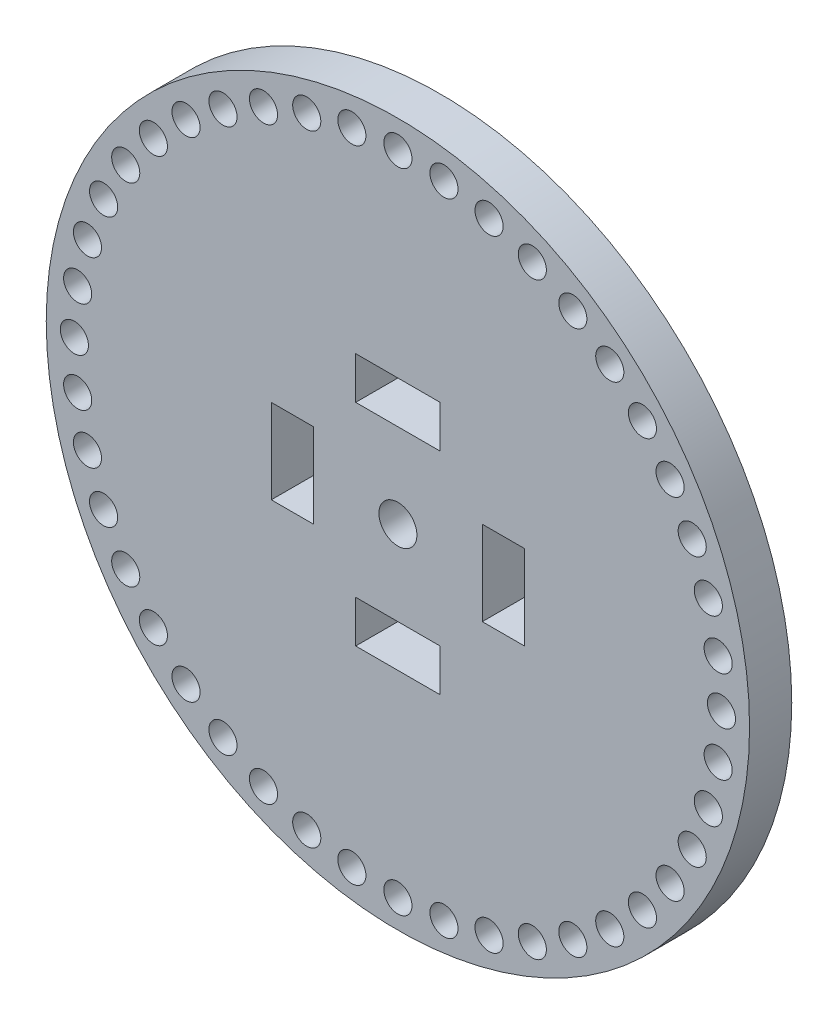
SolidWorks part; units mm, degrees
ref_plane "Front Plane" through (0, 0, 0) normal (0, 0, 1) x (1, 0, 0)
ref_plane "Top Plane" through (0, 0, 0) normal (0, 1, 0) x (1, 0, 0)
ref_plane "Right Plane" through (0, 0, 0) normal (1, 0, 0) x (0, 0, -1)
sketch "Sketch1" plane through (0, 0, 0) normal (0, 0, 1) x (1, 0, 0)
  line L0 (0, 0) -> (0, 9.75) construction
  circle A0 centre (0, 0) radius 25
  point P8 (0, 8.25)
  dimension "D1" = 50
extrude "Boss-Extrude1" add sketch "Sketch1" along normal blind 3
sketch "Sketch6" plane through (0, 0, 3) normal (0, 0, 1) x (1, 0, 0)
  line L0 (0, 0) -> (0, 23) construction
  circle A0 centre (0, 23) radius 1
  circle A1 centre (3.2732, 22.7659) radius 1
  circle A2 centre (6.4798, 22.0683) radius 1
  circle A3 centre (9.5545, 20.9215) radius 1
  circle A4 centre (12.4347, 19.3488) radius 1
  circle A5 centre (15.0618, 17.3822) radius 1
  circle A6 centre (17.3822, 15.0618) radius 1
  circle A7 centre (19.3488, 12.4347) radius 1
  circle A8 centre (20.9215, 9.5545) radius 1
  circle A9 centre (22.0683, 6.4798) radius 1
  circle A10 centre (22.7659, 3.2732) radius 1
  circle A11 centre (23, 0) radius 1
  circle A12 centre (22.7659, -3.2732) radius 1
  circle A13 centre (22.0683, -6.4798) radius 1
  circle A14 centre (20.9215, -9.5545) radius 1
  circle A15 centre (19.3488, -12.4347) radius 1
  circle A16 centre (17.3822, -15.0618) radius 1
  circle A17 centre (15.0618, -17.3822) radius 1
  circle A18 centre (12.4347, -19.3488) radius 1
  circle A19 centre (9.5545, -20.9215) radius 1
  circle A20 centre (6.4798, -22.0683) radius 1
  circle A21 centre (3.2732, -22.7659) radius 1
  circle A22 centre (0, -23) radius 1
  circle A23 centre (-3.2732, -22.7659) radius 1
  circle A24 centre (-6.4798, -22.0683) radius 1
  circle A25 centre (-9.5545, -20.9215) radius 1
  circle A26 centre (-12.4347, -19.3488) radius 1
  circle A27 centre (-15.0618, -17.3822) radius 1
  circle A28 centre (-17.3822, -15.0618) radius 1
  circle A29 centre (-19.3488, -12.4347) radius 1
  circle A30 centre (-20.9215, -9.5545) radius 1
  circle A31 centre (-22.0683, -6.4798) radius 1
  circle A32 centre (-22.7659, -3.2732) radius 1
  circle A33 centre (-23, 0) radius 1
  circle A34 centre (-22.7659, 3.2732) radius 1
  circle A35 centre (-22.0683, 6.4798) radius 1
  circle A36 centre (-20.9215, 9.5545) radius 1
  circle A37 centre (-19.3488, 12.4347) radius 1
  circle A38 centre (-17.3822, 15.0618) radius 1
  circle A39 centre (-15.0618, 17.3822) radius 1
  circle A40 centre (-12.4347, 19.3488) radius 1
  circle A41 centre (-9.5545, 20.9215) radius 1
  circle A42 centre (-6.4798, 22.0683) radius 1
  circle A43 centre (-3.2732, 22.7659) radius 1
  dimension "D2" = 2
  dimension "D1" = 23
  dimension "D3" = 44
extrude "Cut-Extrude3" cut sketch "Sketch6" against normal up to surface (3 mm away) contours A0
sketch "Sketch7" plane through (0, 0, 3) normal (0, 0, 1) x (1, 0, 0)
  circle A0 centre (0, 0) radius 1.35
  dimension "D1" = 2.7
extrude "Cut-Extrude4" cut sketch "Sketch7" against normal up to surface (3 mm away) up to face at (-21.7659, -3.2732, 0)
sketch "Sketch10" plane through (0, 0, 3) normal (0, 0, 1) x (1, 0, 0)
  line L0 (0, 0) -> (0, 9) construction
  line L1 (3, 9) -> (-3, 9)
  line L2 (-3, 9) -> (-3, 6)
  line L3 (-3, 6) -> (3, 6)
  line L4 (3, 9) -> (3, 6)
  line L5 (9, -3) -> (9, 3)
  line L6 (9, 3) -> (6, 3)
  line L7 (6, 3) -> (6, -3)
  line L8 (9, -3) -> (6, -3)
  line L9 (-3, -9) -> (3, -9)
  line L10 (3, -9) -> (3, -6)
  line L11 (3, -6) -> (-3, -6)
  line L12 (-3, -9) -> (-3, -6)
  line L13 (-9, 3) -> (-9, -3)
  line L14 (-9, -3) -> (-6, -3)
  line L15 (-6, -3) -> (-6, 3)
  line L16 (-9, 3) -> (-6, 3)
  point P8 (0, 6)
  dimension "D1" = 3
  dimension "D2" = 3
  dimension "D3" = 9
  dimension "D4" = 4
extrude "Cut-Extrude5" cut sketch "Sketch10" against normal up to surface (3 mm away) up to face at (1.35, 0, 0)
sketch "Sketch11" plane through (0, 0, 3) normal (0, 0, 1) x (1, 0, 0)
  line L0 (0, 0) -> (0, 6.9061) construction
  line L1 (-1.25, 6.9061) -> (1.25, 6.9061)
  line L2 (-1.25, 6.9061) -> (-1.25, 4.4061)
  line L3 (-1.25, 4.4061) -> (1.25, 4.4061)
  line L4 (1.25, 6.9061) -> (1.25, 4.4061)
  line L9 (-1.35, 0) -> (1.35, 0) construction
  line L10 (1.25, -6.9061) -> (1.25, -4.4061)
  line L11 (-1.25, -4.4061) -> (1.25, -4.4061)
  line L12 (-1.25, -6.9061) -> (-1.25, -4.4061)
  line L13 (-1.25, -6.9061) -> (1.25, -6.9061)
  circle A0 centre (0, 0) radius 1.35 construction
  dimension "D1" = 2.5
  dimension "D2" = 2.5
extrude "Cut-Extrude6" [suppressed] cut sketch "Sketch11" against normal up to surface (2.5 mm away)
sketch "Sketch12" plane through (0, 0, 0) normal (0, 0, -1) x (-1, 0, 0)
  circle A0 centre (0, 4) radius 1.35
  circle A1 centre (0, 0) radius 1.35 construction
  dimension "D1" = 2.7
  dimension "D2" = 4
extrude "Cut-Extrude7" [suppressed] cut sketch "Sketch12" against normal up to surface (3 mm away)
